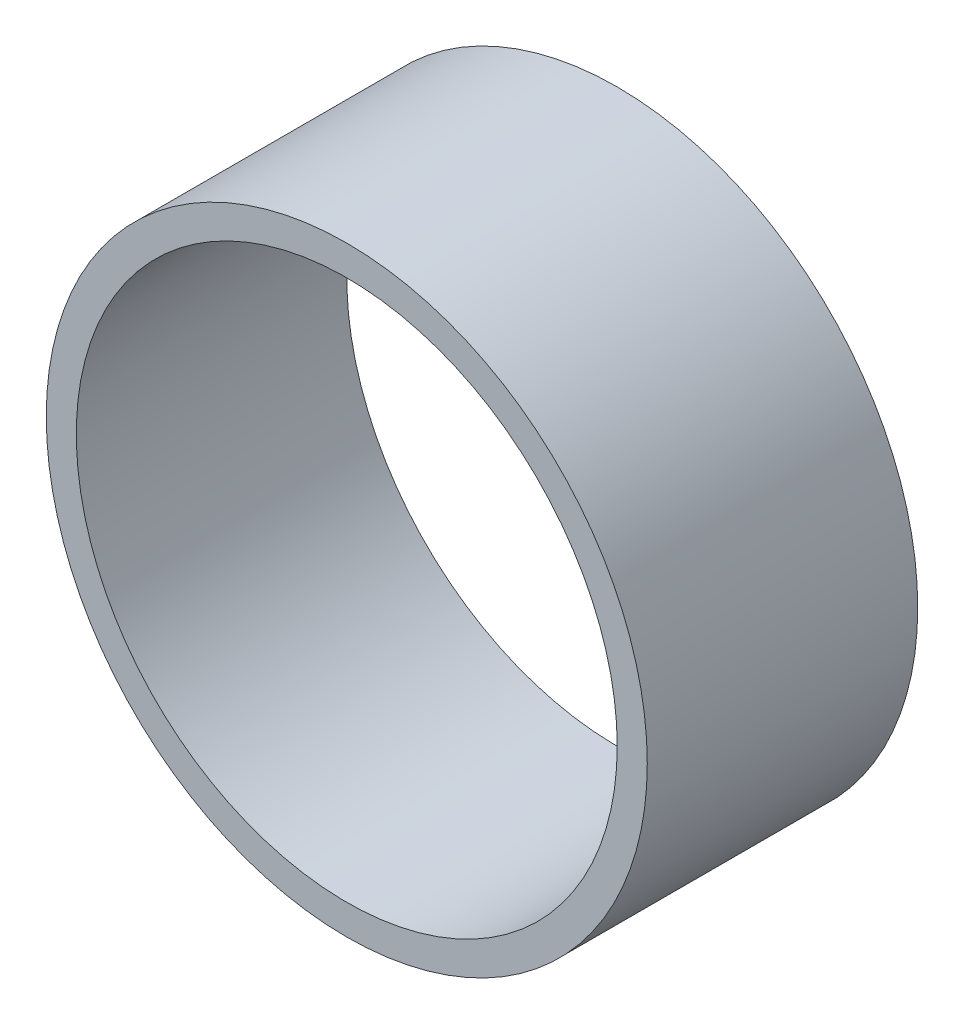
SolidWorks part; units mm, degrees
material "CA"
ref_plane "Front" through (0, 0, 0) normal (0, 0, 1) x (1, 0, 0)
ref_plane "Top" through (0, 0, 0) normal (0, 1, 0) x (1, 0, 0)
ref_plane "Right" through (0, 0, 0) normal (1, 0, 0) x (0, 0, -1)
sketch "Sketch1" plane through (0, 0, 0) normal (0, 0, 1) x (1, 0, 0)
  circle A0 centre (0, 0) radius 10
extrude "Boss-Extrude1" add sketch "Sketch1" along normal blind 9
sketch "Sketch2" plane through (0, 0, 9) normal (0, 0, 1) x (1, 0, 0)
  circle A0 centre (0, 0) radius 9
extrude "Cut-Extrude1" cut sketch "Sketch2" against normal blind 9
